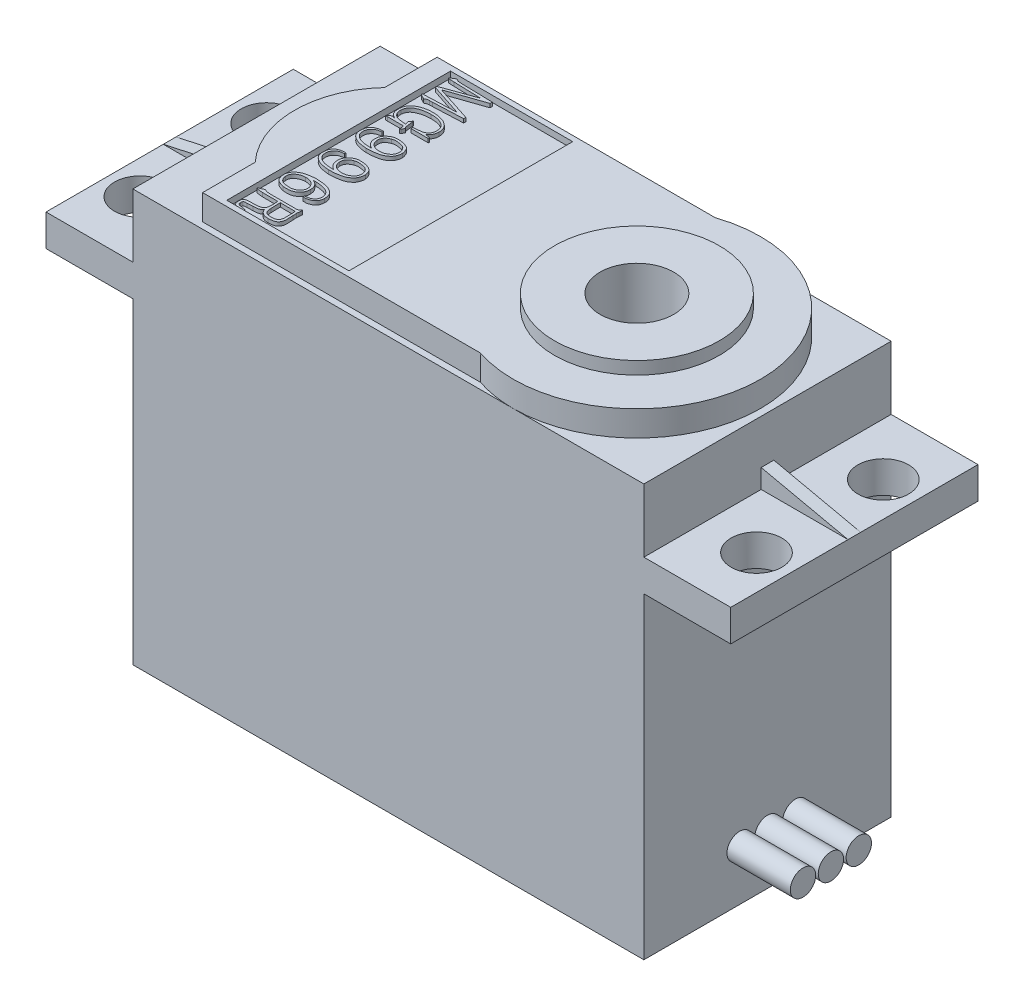
SolidWorks part; units mm, degrees
material "CA"
ref_plane "前视基准面" through (0, 0, 0) normal (0, 0, 1) x (1, 0, 0)
ref_plane "上视基准面" through (0, 0, 0) normal (0, 1, 0) x (1, 0, 0)
ref_plane "右视基准面" through (0, 0, 0) normal (1, 0, 0) x (0, 0, -1)
sketch "草图1" plane through (0, 0, 0) normal (0, 1, 0) x (1, 0, 0)
  line L1 (-20.15, 9.75) -> (20.15, 9.75)
  line L2 (-20.15, 9.75) -> (-20.15, -9.75)
  line L3 (-20.15, -9.75) -> (20.15, -9.75)
  line L4 (20.15, 9.75) -> (20.15, -9.75)
  line L5 (-20.15, 9.75) -> (20.15, -9.75) construction
  line L6 (-20.15, -9.75) -> (20.15, 9.75) construction
  point P0 (0, 0)
  dimension "D1" = 40.3
  dimension "D2" = 19.5
extrude "凸台-拉伸1" add sketch "草图1" along normal blind 27
sketch "草图2" plane through (0, 27, 0) normal (0, 1, 0) x (1, 0, 0)
  line L1 (-27, 9.75) -> (27, 9.75)
  line L2 (-27, 9.75) -> (-27, -9.75)
  line L3 (-27, -9.75) -> (27, -9.75)
  line L4 (27, 9.75) -> (27, -9.75)
  line L5 (-27, 9.75) -> (27, -9.75) construction
  line L6 (-27, -9.75) -> (27, 9.75) construction
  point P0 (0, 0)
  dimension "D1" = 54
  dimension "D2" = 19.5
extrude "凸台-拉伸2" add sketch "草图2" along normal blind 2.5
sketch "草图3" plane through (0, 29.5, 0) normal (0, 1, 0) x (1, 0, 0)
  line L0 (-27, -9.75) -> (27, -9.75) construction
  line L1 (-20.15, 9.75) -> (20.15, 9.75)
  line L2 (-20.15, 9.75) -> (-20.15, -9.75)
  line L3 (-20.15, -9.75) -> (20.15, -9.75)
  line L4 (20.15, 9.75) -> (20.15, -9.75)
  line L5 (-20.15, 9.75) -> (20.15, -9.75) construction
  line L6 (-20.15, -9.75) -> (20.15, 9.75) construction
  line L7 (-27, 9.75) -> (-27, -9.75) construction
  point P0 (0, 0)
  dimension "D1" = 6.85
extrude "凸台-拉伸3" add sketch "草图3" along normal blind 5
sketch "草图4" plane through (0, 34.5, 0) normal (0, 1, 0) x (1, 0, 0)
  line L0 (27, -9.75) -> (27, 9.75) construction
  line L1 (20.15, 9.75) -> (-20.15, 9.75) construction
  line L2 (-28.674, 0) -> (31.5591, 0) construction
  line L3 (-15.15, -9.25) -> (-15.15, -5.099)
  line L4 (-15.15, 9.25) -> (6.7678, 9.25)
  line L5 (-20.15, 9.75) -> (-20.15, -9.75) construction
  line L6 (-15.15, -9.25) -> (6.7678, -9.25)
  line L7 (-20.15, -9.75) -> (20.15, -9.75) construction
  line L8 (-20.15, 9.75) -> (-20.15, -9.75) construction
  line L9 (-15.15, 5.099) -> (-15.15, 9.25)
  arc A0 (6.7678, -9.25) -> (6.7678, 9.25) centre (9.85, 0) ccw
  arc A1 (-15.15, 5.099) -> (-15.15, -5.099) centre (-9.65, 0) ccw
  point P15 (-15.15, 0)
  dimension "D4" = 15
  dimension "D1" = 17.15
  dimension "D2" = 5
  dimension "D3" = 0.5
  dimension "D5" = 10.5
extrude "凸台-拉伸4" add sketch "草图4" along normal blind 2
ref_plane "基准面1" through (0, 0, 0) normal (0, 0, 1) x (1, 0, 0)
sketch "草图5" plane through (0, 0, 0) normal (0, 0, 1) x (1, 0, 0)
  line L2 (20.15, 31) -> (27, 29.5)
  line L3 (20.15, 34.5) -> (20.15, 29.5) construction
  line L4 (20.15, 29.5) -> (27, 29.5) construction
  line L5 (27, 29.5) -> (27, 27) construction
  dimension "D2" = 1.5
rib "筋1" sketch "草图5" sketch "草图5" thickness 1 extrusion direction parallel to sketch draft on no parameters "D1"=1
sketch "草图6" plane through (0, 0, 0) normal (0, 0, 1) x (1, 0, 0)
  line L0 (-20.15, 31) -> (-27, 29.5)
  line L1 (-20.15, 34.5) -> (-20.15, 29.5) construction
  dimension "D1" = 1.5
rib "筋2" sketch "草图6" sketch "草图6" thickness 1 extrusion direction parallel to sketch draft on no parameters "D1"=1
sketch "草图7" plane through (0, 36.5, 0) normal (0, 1, 0) x (1, 0, 0)
  circle A0 centre (9.85, 0) radius 6.5
  dimension "D1" = 13
extrude "凸台-拉伸5" add sketch "草图7" along normal blind 1
sketch "草图8" plane through (0, 37.5, 0) normal (0, 1, 0) x (1, 0, 0)
  circle A0 centre (9.85, 0) radius 2.9
  dimension "D1" = 5.8
extrude "切除-拉伸1" cut sketch "草图8" against normal blind 5
sketch "草图9" plane through (0, 29.5, 0) normal (0, 1, 0) x (1, 0, 0)
  line L0 (-32.7219, 0) -> (36.2848, 0) construction
  line L2 (-27, 9.75) -> (-27, 0.5) construction
  circle A0 centre (-24.35, 5) radius 2
  circle A1 centre (24.28, 5) radius 2
  circle A4 centre (24.28, -5) radius 2
  circle A5 centre (-24.35, -5) radius 2
  dimension "D3" = 4
  dimension "D4" = 4
  dimension "D1" = 5
  dimension "D2" = 5
  dimension "D5" = 48.63
  dimension "D6" = 2.65
extrude "切除-拉伸2" cut sketch "草图9" against normal blind 5
chamfer "倒角1" distance 2 angle 45 4 edges at (-20.15, 0, 0) (0, 0, -9.75) (20.15, 0, 0) (0, 0, 9.75)
sketch "草图10" plane through (0, 36.5, 0) normal (0, 1, 0) x (1, 0, 0)
  line L0 (-17.875, 0) -> (17.875, 0) construction
  line L1 (-13.673, 8.8233) -> (-4.0362, 8.8233)
  line L2 (-13.673, 8.8233) -> (-13.673, -8.8233)
  line L3 (-13.673, -8.8233) -> (-4.0362, -8.8233)
  line L4 (-4.0362, 8.8233) -> (-4.0362, -8.8233)
  line L5 (-13.673, 8.8233) -> (-4.0362, -8.8233) construction
  line L6 (-13.673, -8.8233) -> (-4.0362, 8.8233) construction
  line L7 (-27, 9.75) -> (-27, 0.5) construction
  point P0 (-8.8546, 0)
  dimension "D1" = 13.327
  dimension "D2" = 9.6368
  dimension "D3" = 17.6466
extrude "切除-拉伸3" cut sketch "草图10" against normal blind 0.5
sketch "草图11" plane through (0, 36, 0) normal (0, 1, 0) x (1, 0, 0)
  text T0 "MG996R" font "汉仪长仿宋体" height 3.5
extrude "凸台-拉伸6" add sketch "草图11" along normal blind 0.3
sketch "草图12" plane through (20.15, 0, 0) normal (1, 0, 0) x (0, 0, -1)
  line L0 (9.75, 6.0041) -> (-9.75, 6.0041) construction
  line L1 (9.75, 27) -> (9.75, 2) construction
  line L2 (-9.75, 27) -> (-9.75, 2) construction
  line L3 (11.95, 6.0041) -> (-7.55, 6.0041) construction
  line L4 (0, 6.0041) -> (0, 2) construction
  line L5 (-9.75, 2) -> (9.75, 2) construction
  circle A0 centre (0, 6.0041) radius 1
  circle A1 centre (2.2, 6.0041) radius 1
  circle A2 centre (-2.2, 6.0041) radius 1
  point P9 (3.0235, 6.0041)
  dimension "D1" = 2
  dimension "D2" = 2
  dimension "D4" = 2.2
  dimension "D5" = 2.2
  dimension "D3" = 2
extrude "凸台-拉伸9" add sketch "草图12" along normal blind 5
